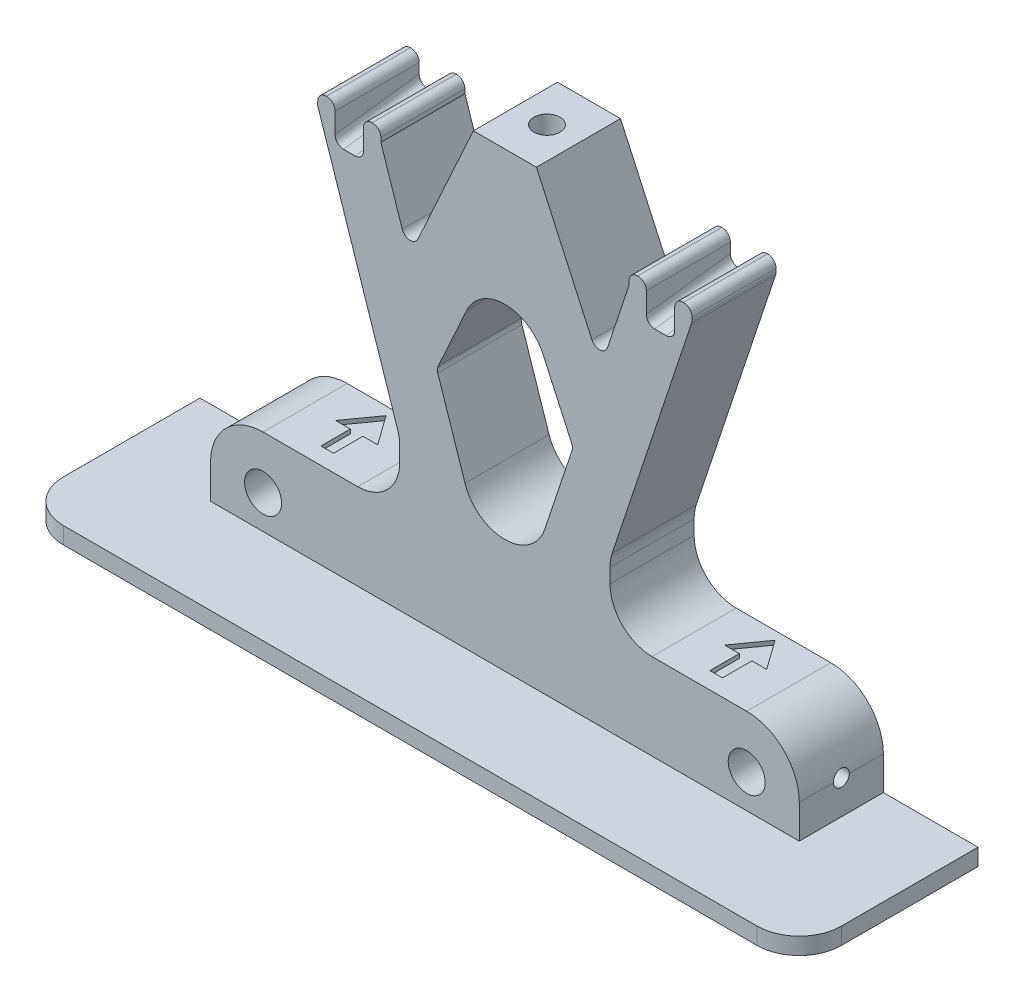
SolidWorks part; units mm, degrees
ref_plane "Front" through (0, 0, 0) normal (0, 0, 1) x (1, 0, 0)
ref_plane "Top" through (0, 0, 0) normal (0, 1, 0) x (1, 0, 0)
ref_plane "Right" through (0, 0, 0) normal (1, 0, 0) x (0, 0, -1)
sketch "Sketch1" plane through (0, 0, 0) normal (0, 0, 1) x (1, 0, 0)
  line L0 (-70, 0) -> (70, 0)
  line L1 (-70, 0) -> (-70, 12)
  line L2 (-57.5, 24.5) -> (-25, 24.5)
  line L3 (-25, 24.5) -> (-25, 39.5)
  line L6 (0, -50) -> (0, 50) construction
  line L8 (25, 24.5) -> (25, 39.5)
  line L9 (57.5, 24.5) -> (25, 24.5)
  line L10 (70, 0) -> (70, 12)
  line L11 (-25, 39.5) -> (-44.5, 98.165)
  line L12 (-44.5, 98.165) -> (-29.5, 98.165)
  line L13 (-29.5, 98.165) -> (0, 9.4154)
  line L14 (29.5, 98.165) -> (0, 9.4154)
  line L15 (44.5, 98.165) -> (29.5, 98.165)
  line L16 (25, 39.5) -> (44.5, 98.165)
  circle A0 centre (-57.5, 12) radius 4.4
  arc A4 (-70, 12) -> (-57.5, 24.5) centre (-57.5, 12) cw
  arc A5 (70, 12) -> (57.5, 24.5) centre (57.5, 12) ccw
  circle A6 centre (57.5, 12) radius 4.4
  point P8 (0, 0)
  point P27 (-37, 98.165)
  point P28 (37, 98.165)
  dimension "D2" = 8.8
  dimension "D1" = 140
  dimension "D3" = 12
  dimension "D4" = 115
  dimension "D5" = 50
  dimension "D6" = 15
  dimension "D7" = 98.165
  dimension "D8" = 15
  dimension "D9" = 74
extrude "Boss-Extrude1" add sketch "Sketch1" along normal blind 20
fillet "Fillet1" radius 10 5 edges at (0, 9.4154, 10) (25, 39.5, 10) (25, 24.5, 10) (-25, 39.5, 10) (-25, 24.5, 10)
sketch "Sketch9" plane through (0, 0, 0) normal (1, 0, 0) x (0, 0, -1)
  line L0 (0, 98.165) -> (-20, 95.665)
  line L1 (-20, 41.0358) -> (-20, 98.165) construction
  line L2 (-20, 98.165) -> (0, 98.165) construction
  dimension "D1" = 2.5
sketch "Sketch2" plane through (0, 0, 0) normal (0, 0, 1) x (1, 0, 0)
  line L2 (44.5, 98.165) -> (29.5, 98.165) construction
  line L3 (40.375, 94.79) -> (33.625, 94.79)
  line L4 (40.375, 94.79) -> (40.375, 101.54)
  line L5 (40.375, 101.54) -> (33.625, 101.54)
  line L6 (33.625, 94.79) -> (33.625, 101.54)
  line L7 (40.375, 94.79) -> (33.625, 101.54) construction
  line L8 (40.375, 101.54) -> (33.625, 94.79) construction
  line L9 (-29.5, 98.165) -> (-44.5, 98.165) construction
  line L10 (-33.625, 94.79) -> (-40.375, 94.79)
  line L11 (-33.625, 94.79) -> (-33.625, 101.54)
  line L12 (-33.625, 101.54) -> (-40.375, 101.54)
  line L13 (-40.375, 94.79) -> (-40.375, 101.54)
  line L14 (-33.625, 94.79) -> (-40.375, 101.54) construction
  line L15 (-33.625, 101.54) -> (-40.375, 94.79) construction
  point P0 (37, 98.165)
  point P7 (-37, 98.165)
  dimension "D1" = 6.75
extrude "Cut-Extrude1" cut sketch "Sketch2" along direction (0, -0.124, 0.9923) on the side of the normal through all
sketch "Sketch3" plane through (0, 98.165, 0) normal (0, 1, 0) x (1, 0, 0)
  line L0 (44.5, 0) -> (40.375, 0) construction
  line L2 (40.375, -20) -> (44.5, -20) construction
  line L3 (44.5, -20) -> (44.5, 0) construction
  line L4 (29.5, -20) -> (33.625, -20) construction
  line L6 (33.625, 0) -> (29.5, 0) construction
  line L7 (29.5, 0) -> (29.5, -20) construction
  line L8 (-29.5, 0) -> (-33.625, 0) construction
  line L10 (-33.625, -20) -> (-29.5, -20) construction
  line L11 (-29.5, -20) -> (-29.5, 0) construction
  line L12 (-44.5, -20) -> (-40.375, -20) construction
  line L14 (-40.375, 0) -> (-44.5, 0) construction
  line L15 (-44.5, 0) -> (-44.5, -20) construction
  line L16 (44.5, 0) -> (40.375, 0)
  line L17 (40.375, 0) -> (40.375, -20)
  line L18 (40.375, -20) -> (44.5, -20)
  line L19 (44.5, -20) -> (44.5, 0)
  line L20 (29.5, -20) -> (33.625, -20)
  line L21 (33.625, -20) -> (33.625, 0)
  line L22 (33.625, 0) -> (29.5, 0)
  line L23 (29.5, 0) -> (29.5, -20)
  line L24 (-29.5, 0) -> (-33.625, 0)
  line L25 (-33.625, 0) -> (-33.625, -20)
  line L26 (-33.625, -20) -> (-29.5, -20)
  line L27 (-29.5, -20) -> (-29.5, 0)
  line L28 (-44.5, -20) -> (-40.375, -20)
  line L29 (-40.375, -20) -> (-40.375, 0)
  line L30 (-40.375, 0) -> (-44.5, 0)
  line L31 (-44.5, 0) -> (-44.5, -20)
extrude "Boss-Extrude2" add sketch "Sketch3" along normal blind 3
fillet "Fillet2" radius 2 13 edges at (-44.5, 101.165, 10) (-40.375, 101.165, 10) (-33.625, 101.165, 10) (-29.5, 101.165, 10) (29.5, 101.165, 10) (33.625, 101.165, 10) (40.375, 101.165, 10) (44.5, 101.165, 10) (44.5, 98.165, 10) (-33.625, 93.54, 10) (-40.375, 93.54, 10) (33.625, 93.54, 10) (40.375, 93.54, 10)
sketch "Sketch4" plane through (0, 0, 20) normal (0, 0, 1) x (1, 0, 0)
  line L0 (-22.7932, 77.9879) -> (-7.5, 111.54)
  line L2 (-38.2459, 79.3497) -> (-24.7383, 83.8396) construction
  line L3 (-44.5, 98.165) -> (-25.5105, 41.0358) construction
  line L10 (-9.4895, 37.9642) -> (-29.5, 98.165) construction
  line L11 (-7.5, 111.54) -> (7.5, 111.54)
  line L12 (7.5, 111.54) -> (22.7932, 77.9879)
  line L13 (29.5, 98.165) -> (9.4895, 37.9642) construction
  line L14 (22.7932, 77.9879) -> (16.1963, 58.1413)
  line L15 (16.1963, 58.1413) -> (0, 93.6746)
  line L16 (0, 93.6746) -> (-16.1963, 58.1413)
  line L17 (-16.1963, 58.1413) -> (-22.7932, 77.9879)
  line L18 (-16.9931, 90.7128) -> (-4.0409, 84.8091) construction
  line L19 (-38.375, 94.79) -> (-35.625, 94.79) construction
  point P13 (0, 111.54)
  point P16 (19.4947, 68.0646)
  point P17 (19.4947, 68.0646)
  dimension "D1" = 16.75
  dimension "D2" = 15
extrude "Boss-Extrude3" add sketch "Sketch4" against normal up to surface (20 mm away) up to face at (-53.1, 12, 0)
fillet "Fillet3" radius 10 1 edges at (0, 93.6746, 10)
fillet "Fillet4" radius 2 4 edges at (-22.7932, 77.9879, 10) (22.7932, 77.9879, 10) (16.1963, 58.1413, 10) (-16.1963, 58.1413, 10)
sketch "Sketch5" plane through (0, 111.54, 0) normal (0, 1, 0) x (1, 0, 0)
  line L0 (7.5, 0) -> (7.5, -20) construction
  circle A0 centre (0, -10) radius 3.1
  point P5 (7.5, -10)
  dimension "D1" = 6.2
extrude "Cut-Extrude2" cut sketch "Sketch5" against normal blind 15
sketch "Sketch6" plane through (0, 0, 0) normal (0, 0, -1) x (-1, 0, 0)
  line L0 (70, 12) -> (70, 0) construction
  line L1 (92.5, 0) -> (-92.5, 0)
  line L2 (92.5, 0) -> (92.5, 4)
  line L3 (92.5, 4) -> (-92.5, 4)
  line L4 (-92.5, 0) -> (-92.5, 4)
  point P4 (0, 0)
  dimension "D1" = 22.5
  dimension "D2" = 4
extrude "Boss-Extrude4" add sketch "Sketch6" against normal offset from surface (42.5 mm away) 22.5 up to face at (0.9066, 76.3845, 20) offset beyond the face yes
fillet "Fillet5" radius 10 2 edges at (92.5, 2, 42.5) (-92.5, 2, 42.5)
sketch "Sketch7" plane through (0, 24.5, 0) normal (0, 1, 0) x (1, 0, 0)
  line L0 (41.25, -9) -> (46.25, -2)
  line L1 (46.25, -2) -> (51.25, -9)
  line L2 (51.25, -9) -> (47.75, -9)
  line L3 (47.75, -9) -> (47.75, -16)
  line L4 (47.75, -16) -> (44.75, -16)
  line L5 (44.75, -16) -> (44.75, -9)
  line L6 (44.75, -9) -> (41.25, -9)
  line L7 (57.5, -20) -> (35, -20) construction
  point P6 (46.25, -16)
  point P10 (46.25, -20)
  dimension "D1" = 3
  dimension "D2" = 14
  dimension "D3" = 10
  dimension "D4" = 7
  dimension "D5" = 4
extrude "Cut-Extrude3" cut sketch "Sketch7" against normal blind 1
sketch "Sketch8" plane through (70, 0, 0) normal (1, 0, 0) x (0, 0, -1)
  line L0 (-20, 12) -> (0, 12) construction
  circle A0 centre (-10, 12) radius 1.9
  dimension "D1" = 3.8
extrude "Cut-Extrude4" cut sketch "Sketch8" against normal blind 10
mirror "Mirror1" about plane through (0, 0, 0) normal (1, 0, 0) of "Cut-Extrude4", "Cut-Extrude3"
